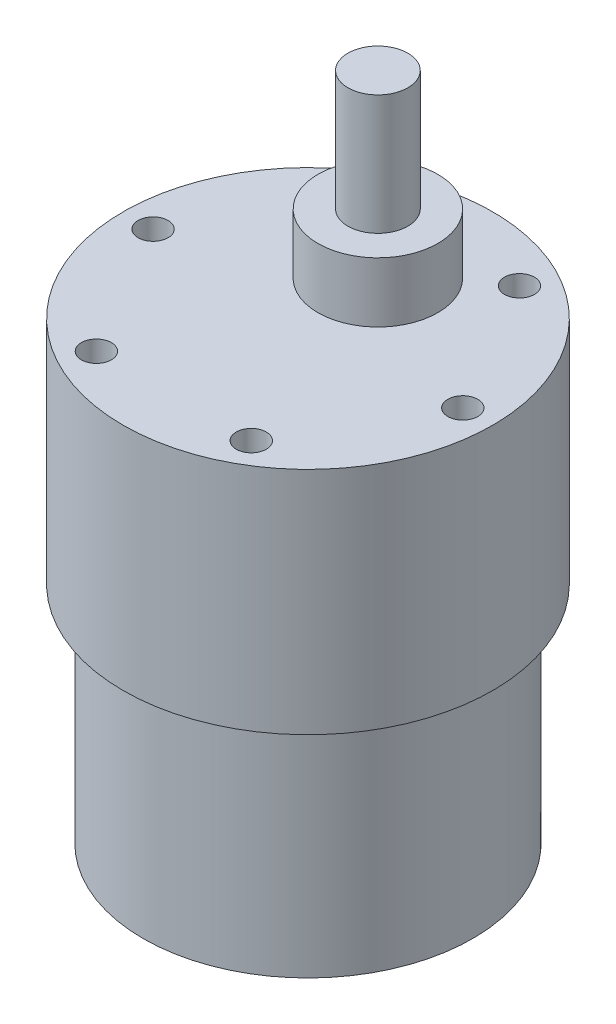
SolidWorks part; units mm, degrees
ref_plane "前视基准面" through (0, 0, 0) normal (0, 0, 1) x (1, 0, 0)
ref_plane "上视基准面" through (0, 0, 0) normal (0, 1, 0) x (1, 0, 0)
ref_plane "右视基准面" through (0, 0, 0) normal (1, 0, 0) x (0, 0, -1)
sketch "草图1" plane through (0, 0, 0) normal (0, 1, 0) x (1, 0, 0)
  circle A0 centre (0, 0) radius 18.5
  dimension "D1" = 37
extrude "凸台-拉伸1" add sketch "草图1" against normal blind 23
sketch "草图2" plane through (0, -23, 0) normal (0, -1, 0) x (1, 0, 0)
  circle A0 centre (0, 0) radius 16.5
  dimension "D1" = 33
extrude "凸台-拉伸2" add sketch "草图2" along normal blind 22.5
sketch "草图3" plane through (0, 0, 0) normal (0, 1, 0) x (1, 0, 0)
  line L0 (-27.5769, 0) -> (29.2546, 0) construction
  circle A0 centre (0, 0) radius 15.5 construction
  circle A1 centre (-15.5, 0) radius 1.5
  circle A2 centre (-7.75, 13.4234) radius 1.5
  circle A3 centre (7.75, 13.4234) radius 1.5
  circle A4 centre (15.5, 0) radius 1.5
  circle A5 centre (7.75, -13.4234) radius 1.5
  circle A6 centre (-7.75, -13.4234) radius 1.5
  point P20 (0, 0)
  dimension "D1" = 3
  dimension "D2" = 31
  dimension "D3" = 6
extrude "切除-拉伸1" cut sketch "草图3" against normal blind 10
sketch "草图4" plane through (0, 0, 0) normal (0, 1, 0) x (1, 0, 0)
  line L0 (0, -12.1632) -> (0, 14.1205) construction
  circle A0 centre (0, 7) radius 6
  dimension "D1" = 12
  dimension "D2" = 7
extrude "凸台-拉伸3" add sketch "草图4" along normal blind 6
sketch "草图5" plane through (0, 6, 0) normal (0, 1, 0) x (1, 0, 0)
  circle A0 centre (0, 7) radius 3
  dimension "D1" = 6
extrude "凸台-拉伸4" add sketch "草图5" along normal blind 12
